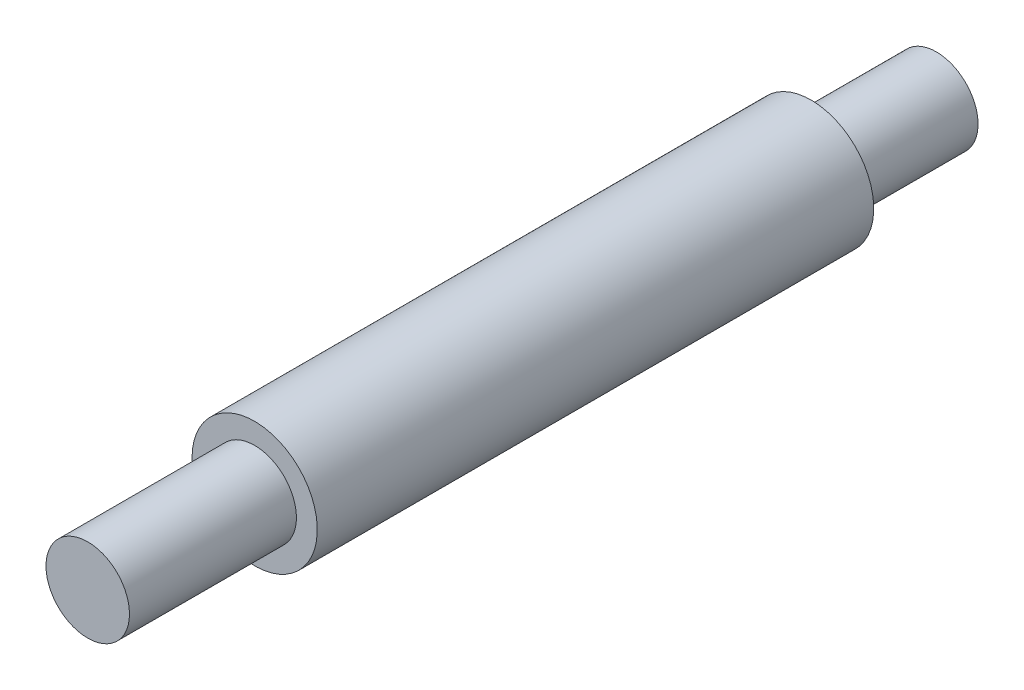
SolidWorks part; units mm, degrees
material "Aluminum"
ref_plane "Front Plane" through (0, 0, 0) normal (0, 0, 1) x (1, 0, 0)
ref_plane "Top Plane" through (0, 0, 0) normal (0, 1, 0) x (1, 0, 0)
ref_plane "Right Plane" through (0, 0, 0) normal (1, 0, 0) x (0, 0, -1)
sketch "Sketch1" plane through (0, 0, 0) normal (0, 0, 1) x (1, 0, 0)
  circle A0 centre (0, 0) radius 1.5
  dimension "D1" = 3
extrude "Boss-Extrude1" add sketch "Sketch1" along normal blind 6
sketch "Sketch2" plane through (0, 0, 0) normal (0, 0, -1) x (-1, 0, 0)
  circle A0 centre (0, 0) radius 2.25
  dimension "D1" = 4.5
extrude "Boss-Extrude2" add sketch "Sketch2" along normal blind 20
sketch "Sketch3" plane through (0, 0, -20) normal (0, 0, -1) x (-1, 0, 0)
  circle A0 centre (0, 0) radius 1.5
  dimension "D1" = 3
extrude "Boss-Extrude3" add sketch "Sketch3" along normal blind 4.5
